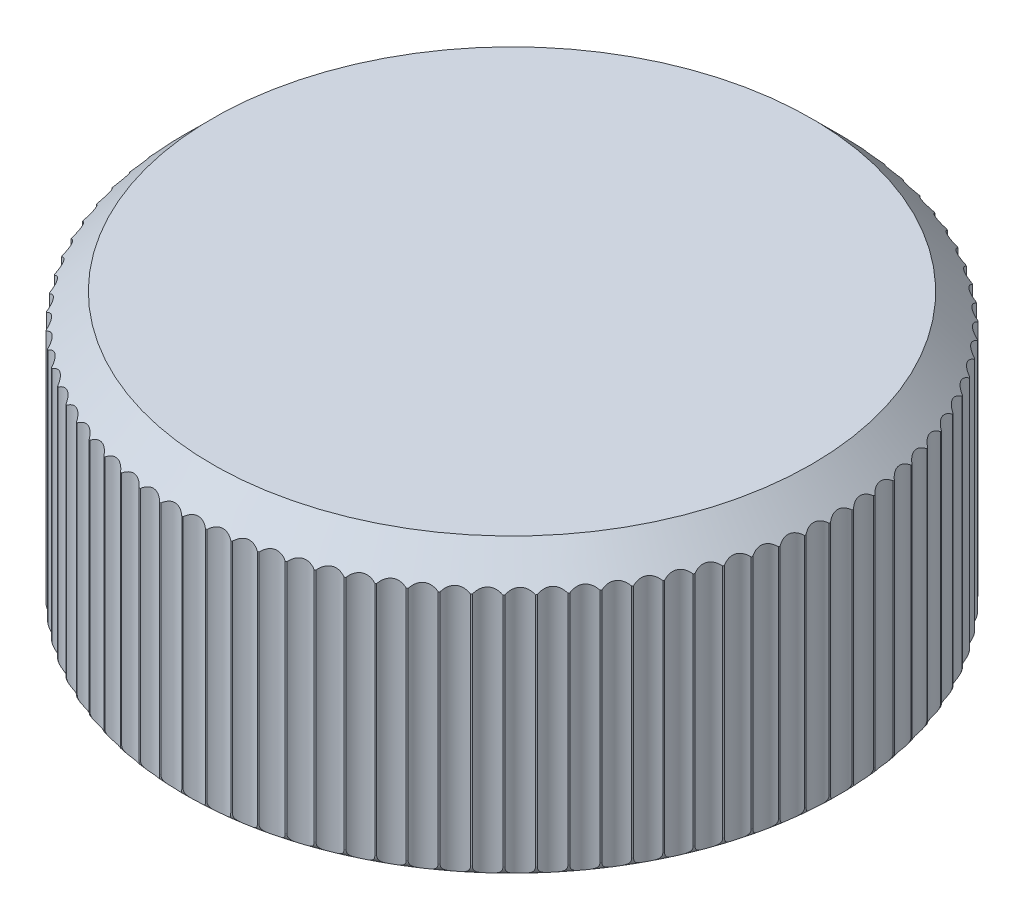
SolidWorks part; units mm, degrees
ref_plane "Ebene vorne" through (0, 0, 0) normal (0, 0, 1) x (1, 0, 0)
ref_plane "Ebene oben" through (0, 0, 0) normal (0, 1, 0) x (1, 0, 0)
ref_plane "Ebene rechts" through (0, 0, 0) normal (1, 0, 0) x (0, 0, -1)
sketch "Skizze1" plane through (0, 0, 0) normal (0, 0, 1) x (1, 0, 0)
  line L0 (0, 8) -> (0, 13.8)
  line L1 (0, 13.8) -> (-15, 13.8)
  line L2 (-16.5, 12.3) -> (-16.5, 0.5)
  line L3 (-16, 0) -> (-15, 0)
  line L4 (-14.5, 0.5) -> (-14.5, 5.5)
  line L5 (-14, 6) -> (-6, 6)
  line L6 (-5.5, 5.5) -> (-5.5, 0.5)
  line L7 (-5, 0) -> (-3, 0)
  line L8 (-3, 0) -> (-3, 7.5)
  line L9 (-2.5, 8) -> (0, 8)
  line L10 (-15, 13.8) -> (-16.5, 12.3)
  arc A0 (-3, 7.5) -> (-2.5, 8) centre (-2.5, 7.5) cw
  arc A1 (-5.5, 0.5) -> (-5, 0) centre (-5, 0.5) ccw
  arc A2 (-6, 6) -> (-5.5, 5.5) centre (-6, 5.5) cw
  arc A3 (-14.5, 5.5) -> (-14, 6) centre (-14, 5.5) cw
  arc A4 (-15, 0) -> (-14.5, 0.5) centre (-15, 0.5) ccw
  arc A5 (-16.5, 0.5) -> (-16, 0) centre (-16, 0.5) ccw
  point P3 (-16.5, 13.8)
  dimension "D1" = 0.5
revolve "Rotation1" add sketch "Skizze1" angle 360 about L0
sketch "Skizze2" plane through (0, 13.8, 0) normal (0, 1, 0) x (1, 0, 0)
  circle A0 centre (0, 0) radius 18.5117
  arc A1 (16.5206, 0.5769) -> (16.5206, -0.5769) centre (17.1752, 0) ccw
  arc A2 (16.5206, -0.5769) -> (16.4401, -1.7279) centre (17.1334, -1.1981) ccw
  arc A3 (16.4401, -1.7279) -> (16.2795, -2.8705) centre (17.0081, -2.3903) ccw
  arc A4 (16.2795, -2.8705) -> (16.0396, -3.9991) centre (16.7999, -3.5709) ccw
  arc A16 (8.7599, -14.0188) -> (7.7607, -14.5957) centre (8.5876, -14.8742) ccw
  arc A17 (7.7607, -14.5957) -> (6.7236, -15.1015) centre (7.5291, -15.437) ccw
  arc A40 (-14.8576, -7.2466) -> (-15.3269, -6.1925) centre (-15.6903, -6.9858) ccw
  arc A41 (-15.3269, -6.1925) -> (-15.7216, -5.1082) centre (-16.1394, -5.8743) ccw
  arc A76 (7.7607, 14.5957) -> (8.7599, 14.0188) centre (8.5876, 14.8742) ccw
  arc A77 (8.7599, 14.0188) -> (9.7165, 13.3736) centre (9.6042, 14.2389) ccw
  arc A78 (9.7165, 13.3736) -> (10.6257, 12.6632) centre (10.5741, 13.5342) ccw
  arc A83 (13.7045, 9.2438) -> (14.3159, 8.2653) centre (14.5654, 9.1015) ccw
  arc A84 (14.3159, 8.2653) -> (14.8576, 7.2466) centre (15.1648, 8.0633) ccw
  arc A89 (16.2795, 2.8705) -> (16.4401, 1.7279) centre (17.0081, 2.3903) ccw
  arc A90 (16.4401, 1.7279) -> (16.5206, 0.5769) centre (17.1334, 1.1981) ccw
  arc A91 (6.7236, 15.1015) -> (7.7607, 14.5957) centre (7.5291, 15.437) ccw
  arc A92 (5.6538, 15.5337) -> (6.7236, 15.1015) centre (6.4339, 15.9246) ccw
  arc A93 (4.5565, 15.8903) -> (5.6538, 15.5337) centre (5.3074, 16.3346) ccw
  arc A94 (3.4369, 16.1694) -> (4.5565, 15.8903) centre (4.1551, 16.665) ccw
  arc A95 (2.3006, 16.3698) -> (3.4369, 16.1694) centre (2.9824, 16.9143) ccw
  arc A96 (1.1531, 16.4904) -> (2.3006, 16.3698) centre (1.7953, 17.0811) ccw
  arc A97 (0, 16.5306) -> (1.1531, 16.4904) centre (0.5994, 17.1647) ccw
  arc A98 (-1.1531, 16.4904) -> (0, 16.5306) centre (-0.5994, 17.1647) ccw
  arc A99 (-2.3006, 16.3698) -> (-1.1531, 16.4904) centre (-1.7953, 17.0811) ccw
  arc A100 (-3.4369, 16.1694) -> (-2.3006, 16.3698) centre (-2.9824, 16.9143) ccw
  arc A101 (-4.5565, 15.8903) -> (-3.4369, 16.1694) centre (-4.1551, 16.665) ccw
  arc A102 (-5.6538, 15.5337) -> (-4.5565, 15.8903) centre (-5.3074, 16.3346) ccw
  arc A103 (-6.7236, 15.1015) -> (-5.6538, 15.5337) centre (-6.4339, 15.9246) ccw
  arc A104 (-7.7607, 14.5957) -> (-6.7236, 15.1015) centre (-7.5291, 15.437) ccw
  arc A105 (-8.7599, 14.0188) -> (-7.7607, 14.5957) centre (-8.5876, 14.8742) ccw
  arc A106 (-9.7165, 13.3736) -> (-8.7599, 14.0188) centre (-9.6042, 14.2389) ccw
  arc A107 (-10.6257, 12.6632) -> (-9.7165, 13.3736) centre (-10.5741, 13.5342) ccw
  arc A108 (-11.4831, 11.8911) -> (-10.6257, 12.6632) centre (-11.4925, 12.7637) ccw
  arc A109 (-12.2847, 11.0611) -> (-11.4831, 11.8911) centre (-12.3548, 11.9309) ccw
  arc A110 (-13.0263, 10.1773) -> (-12.2847, 11.0611) centre (-13.157, 11.04) ccw
  arc A111 (-13.7045, 9.2438) -> (-13.0263, 10.1773) centre (-13.895, 10.0953) ccw
  arc A112 (-14.3159, 8.2653) -> (-13.7045, 9.2438) centre (-14.5654, 9.1015) ccw
  arc A113 (-14.8576, 7.2466) -> (-14.3159, 8.2653) centre (-15.1648, 8.0633) ccw
  arc A114 (-15.3269, 6.1925) -> (-14.8576, 7.2466) centre (-15.6903, 6.9858) ccw
  arc A115 (-15.7216, 5.1082) -> (-15.3269, 6.1925) centre (-16.1394, 5.8743) ccw
  arc A116 (-16.0396, 3.9991) -> (-15.7216, 5.1082) centre (-16.5099, 4.7341) ccw
  arc A117 (-16.2795, 2.8705) -> (-16.0396, 3.9991) centre (-16.7999, 3.5709) ccw
  arc A118 (-16.4401, 1.7279) -> (-16.2795, 2.8705) centre (-17.0081, 2.3903) ccw
  arc A119 (-16.5206, 0.5769) -> (-16.4401, 1.7279) centre (-17.1334, 1.1981) ccw
  arc A120 (-16.5206, -0.5769) -> (-16.5206, 0.5769) centre (-17.1752, 0) ccw
  arc A121 (-16.4401, -1.7279) -> (-16.5206, -0.5769) centre (-17.1334, -1.1981) ccw
  arc A122 (-16.2795, -2.8705) -> (-16.4401, -1.7279) centre (-17.0081, -2.3903) ccw
  arc A123 (-16.0396, -3.9991) -> (-16.2795, -2.8705) centre (-16.7999, -3.5709) ccw
  arc A124 (-15.7216, -5.1082) -> (-16.0396, -3.9991) centre (-16.5099, -4.7341) ccw
  arc A125 (-14.3159, -8.2653) -> (-14.8576, -7.2466) centre (-15.1648, -8.0633) ccw
  arc A126 (-13.7045, -9.2438) -> (-14.3159, -8.2653) centre (-14.5654, -9.1015) ccw
  arc A127 (-13.0263, -10.1773) -> (-13.7045, -9.2438) centre (-13.895, -10.0953) ccw
  arc A128 (-12.2847, -11.0611) -> (-13.0263, -10.1773) centre (-13.157, -11.04) ccw
  arc A129 (-17.2701, -4.3059) -> (-16.2603, -5.5703) centre (-16.5099, -4.7341) ccw [skipped]
  arc A130 (-11.4831, -11.8911) -> (-12.2847, -11.0611) centre (-12.3548, -11.9309) ccw
  arc A131 (-10.6257, -12.6632) -> (-11.4831, -11.8911) centre (-11.4925, -12.7637) ccw
  arc A132 (-9.7165, -13.3736) -> (-10.6257, -12.6632) centre (-10.5741, -13.5342) ccw
  arc A133 (-8.7599, -14.0188) -> (-9.7165, -13.3736) centre (-9.6042, -14.2389) ccw
  arc A134 (-7.7607, -14.5957) -> (-8.7599, -14.0188) centre (-8.5876, -14.8742) ccw
  arc A135 (-6.7236, -15.1015) -> (-7.7607, -14.5957) centre (-7.5291, -15.437) ccw
  arc A136 (-5.6538, -15.5337) -> (-6.7236, -15.1015) centre (-6.4339, -15.9246) ccw
  arc A137 (-4.5565, -15.8903) -> (-5.6538, -15.5337) centre (-5.3074, -16.3346) ccw
  arc A138 (-3.4369, -16.1694) -> (-4.5565, -15.8903) centre (-4.1551, -16.665) ccw
  arc A139 (-2.3006, -16.3698) -> (-3.4369, -16.1694) centre (-2.9824, -16.9143) ccw
  arc A140 (-1.1531, -16.4904) -> (-2.3006, -16.3698) centre (-1.7953, -17.0811) ccw
  arc A141 (0, -16.5306) -> (-1.1531, -16.4904) centre (-0.5994, -17.1647) ccw
  arc A142 (1.1531, -16.4904) -> (0, -16.5306) centre (0.5994, -17.1647) ccw
  arc A143 (2.3006, -16.3698) -> (1.1531, -16.4904) centre (1.7953, -17.0811) ccw
  arc A144 (3.4369, -16.1694) -> (2.3006, -16.3698) centre (2.9824, -16.9143) ccw
  arc A145 (4.5565, -15.8903) -> (3.4369, -16.1694) centre (4.1551, -16.665) ccw
  arc A146 (5.6538, -15.5337) -> (4.5565, -15.8903) centre (5.3074, -16.3346) ccw
  arc A147 (6.7236, -15.1015) -> (5.6538, -15.5337) centre (6.4339, -15.9246) ccw
  arc A148 (9.7165, -13.3736) -> (8.7599, -14.0188) centre (9.6042, -14.2389) ccw
  arc A149 (10.6257, -12.6632) -> (9.7165, -13.3736) centre (10.5741, -13.5342) ccw
  arc A150 (11.4831, -11.8911) -> (10.6257, -12.6632) centre (11.4925, -12.7637) ccw
  arc A151 (12.2847, -11.0611) -> (11.4831, -11.8911) centre (12.3548, -11.9309) ccw
  arc A152 (13.0263, -10.1773) -> (12.2847, -11.0611) centre (13.157, -11.04) ccw
  arc A153 (13.7045, -9.2438) -> (13.0263, -10.1773) centre (13.895, -10.0953) ccw
  arc A154 (14.3159, -8.2653) -> (13.7045, -9.2438) centre (14.5654, -9.1015) ccw
  arc A155 (14.8576, -7.2466) -> (14.3159, -8.2653) centre (15.1648, -8.0633) ccw
  arc A156 (15.3269, -6.1925) -> (14.8576, -7.2466) centre (15.6903, -6.9858) ccw
  arc A157 (15.7216, -5.1082) -> (15.3269, -6.1925) centre (16.1394, -5.8743) ccw
  arc A158 (16.0396, -3.9991) -> (15.7216, -5.1082) centre (16.5099, -4.7341) ccw
  arc A159 (16.0396, 3.9991) -> (16.2795, 2.8705) centre (16.7999, 3.5709) ccw
  arc A160 (15.7216, 5.1082) -> (16.0396, 3.9991) centre (16.5099, 4.7341) ccw
  arc A161 (15.3269, 6.1925) -> (15.7216, 5.1082) centre (16.1394, 5.8743) ccw
  arc A162 (14.8576, 7.2466) -> (15.3269, 6.1925) centre (15.6903, 6.9858) ccw
  arc A163 (13.0263, 10.1773) -> (13.7045, 9.2438) centre (13.895, 10.0953) ccw
  arc A164 (12.2847, 11.0611) -> (13.0263, 10.1773) centre (13.157, 11.04) ccw
  arc A165 (11.4831, 11.8911) -> (12.2847, 11.0611) centre (12.3548, 11.9309) ccw
  arc A166 (10.6257, 12.6632) -> (11.4831, 11.8911) centre (11.4925, 12.7637) ccw
  arc A167 (13.2271, 11.9098) -> (12.3641, 12.8034) centre (12.3548, 11.9309) ccw [skipped]
  arc A168 (12.3641, 12.8034) -> (11.4409, 13.6347) centre (11.4925, 12.7637) ccw [skipped]
  arc A169 (14.0257, 10.9581) -> (13.2271, 11.9098) centre (13.157, 11.04) ccw [skipped]
  arc A170 (14.7559, 9.953) -> (14.0257, 10.9581) centre (13.895, 10.0953) ccw [skipped]
  arc A171 (16.5028, 6.6676) -> (15.9975, 7.8025) centre (15.6903, 6.9858) ccw [skipped]
  arc A172 (16.9277, 5.5001) -> (16.5028, 6.6676) centre (16.1394, 5.8743) ccw [skipped]
  arc A173 (17.2701, 4.3059) -> (16.9277, 5.5001) centre (16.5099, 4.7341) ccw [skipped]
  arc A174 (17.5284, 3.0907) -> (17.2701, 4.3059) centre (16.7999, 3.5709) ccw [skipped]
  arc A175 (16.9277, -5.5001) -> (17.2701, -4.3059) centre (16.5099, -4.7341) ccw [skipped]
  arc A176 (16.5028, -6.6676) -> (16.9277, -5.5001) centre (16.1394, -5.8743) ccw [skipped]
  arc A177 (15.9975, -7.8025) -> (16.5028, -6.6676) centre (15.6903, -6.9858) ccw [skipped]
  arc A178 (15.4143, -8.8994) -> (15.9975, -7.8025) centre (15.1648, -8.0633) ccw [skipped]
  arc A179 (14.7559, -9.953) -> (15.4143, -8.8994) centre (14.5654, -9.1015) ccw [skipped]
  arc A180 (14.0257, -10.9581) -> (14.7559, -9.953) centre (13.895, -10.0953) ccw [skipped]
  arc A181 (13.2271, -11.9098) -> (14.0257, -10.9581) centre (13.157, -11.04) ccw [skipped]
  arc A182 (12.3641, -12.8034) -> (13.2271, -11.9098) centre (12.3548, -11.9309) ccw [skipped]
  arc A183 (11.4409, -13.6347) -> (12.3641, -12.8034) centre (11.4925, -12.7637) ccw [skipped]
  arc A184 (10.4619, -14.3996) -> (11.4409, -13.6347) centre (10.5741, -13.5342) ccw [skipped]
  arc A185 (9.4319, -15.0943) -> (10.4619, -14.3996) centre (9.6042, -14.2389) ccw [skipped]
  arc A186 (4.906, -17.1093) -> (6.0876, -16.7254) centre (5.3074, -16.3346) ccw [skipped]
  arc A187 (3.7006, -17.4099) -> (4.906, -17.1093) centre (4.1551, -16.665) ccw [skipped]
  arc A188 (2.4771, -17.6256) -> (3.7006, -17.4099) centre (2.9824, -16.9143) ccw [skipped]
  arc A189 (1.2416, -17.7555) -> (2.4771, -17.6256) centre (1.7953, -17.0811) ccw [skipped]
  arc A190 (0, -17.7988) -> (1.2416, -17.7555) centre (0.5994, -17.1647) ccw [skipped]
  arc A191 (-1.2416, -17.7555) -> (0, -17.7988) centre (-0.5994, -17.1647) ccw [skipped]
  arc A192 (6.0876, -16.7254) -> (7.2394, -16.2601) centre (6.4339, -15.9246) ccw [skipped]
  arc A193 (-2.4771, -17.6256) -> (-1.2416, -17.7555) centre (-1.7953, -17.0811) ccw [skipped]
  arc A194 (-3.7006, -17.4099) -> (-2.4771, -17.6256) centre (-2.9824, -16.9143) ccw [skipped]
  arc A195 (-4.906, -17.1093) -> (-3.7006, -17.4099) centre (-4.1551, -16.665) ccw [skipped]
  arc A196 (-15.9975, -7.8025) -> (-15.4143, -8.8994) centre (-15.1648, -8.0633) ccw [skipped]
  arc A197 (-6.0876, -16.7254) -> (-4.906, -17.1093) centre (-5.3074, -16.3346) ccw [skipped]
  arc A198 (-7.2394, -16.2601) -> (-6.0876, -16.7254) centre (-6.4339, -15.9246) ccw [skipped]
  arc A199 (-8.3561, -15.7154) -> (-7.2394, -16.2601) centre (-7.5291, -15.437) ccw [skipped]
  arc A200 (-9.4319, -15.0943) -> (-8.3561, -15.7154) centre (-8.5876, -14.8742) ccw [skipped]
  arc A201 (-10.4619, -14.3996) -> (-9.4319, -15.0943) centre (-9.6042, -14.2389) ccw [skipped]
  arc A202 (-11.4409, -13.6347) -> (-10.4619, -14.3996) centre (-10.5741, -13.5342) ccw [skipped]
  arc A203 (-12.3641, -12.8034) -> (-11.4409, -13.6347) centre (-11.4925, -12.7637) ccw [skipped]
  arc A204 (-13.2271, -11.9098) -> (-12.3641, -12.8034) centre (-12.3548, -11.9309) ccw [skipped]
  arc A205 (-14.0257, -10.9581) -> (-13.2271, -11.9098) centre (-13.157, -11.04) ccw [skipped]
  arc A206 (-14.7559, -9.953) -> (-14.0257, -10.9581) centre (-13.895, -10.0953) ccw [skipped]
  arc A207 (-15.4143, -8.8994) -> (-14.7559, -9.953) centre (-14.5654, -9.1015) ccw [skipped]
  arc A208 (-17.5284, -3.0907) -> (-17.2701, -4.3059) centre (-16.7999, -3.5709) ccw [skipped]
  arc A209 (-17.7013, -1.8605) -> (-17.5284, -3.0907) centre (-17.0081, -2.3903) ccw [skipped]
  arc A210 (-17.788, -0.6212) -> (-17.7013, -1.8605) centre (-17.1334, -1.1981) ccw [skipped]
  arc A211 (-17.788, 0.6212) -> (-17.788, -0.6212) centre (-17.1752, 0) ccw [skipped]
  arc A212 (-17.7013, 1.8605) -> (-17.788, 0.6212) centre (-17.1334, 1.1981) ccw [skipped]
  arc A213 (-17.5284, 3.0907) -> (-17.7013, 1.8605) centre (-17.0081, 2.3903) ccw [skipped]
  arc A214 (-17.2701, 4.3059) -> (-17.5284, 3.0907) centre (-16.7999, 3.5709) ccw [skipped]
  arc A215 (-16.9277, 5.5001) -> (-17.2701, 4.3059) centre (-16.5099, 4.7341) ccw [skipped]
  arc A216 (-16.5028, 6.6676) -> (-16.9277, 5.5001) centre (-16.1394, 5.8743) ccw [skipped]
  arc A217 (-15.9975, 7.8025) -> (-16.5028, 6.6676) centre (-15.6903, 6.9858) ccw [skipped]
  arc A218 (-15.4143, 8.8994) -> (-15.9975, 7.8025) centre (-15.1648, 8.0633) ccw [skipped]
  arc A219 (-14.7559, 9.953) -> (-15.4143, 8.8994) centre (-14.5654, 9.1015) ccw [skipped]
  arc A220 (-14.0257, 10.9581) -> (-14.7559, 9.953) centre (-13.895, 10.0953) ccw [skipped]
  arc A221 (-13.2271, 11.9098) -> (-14.0257, 10.9581) centre (-13.157, 11.04) ccw [skipped]
  arc A222 (-12.3641, 12.8034) -> (-13.2271, 11.9098) centre (-12.3548, 11.9309) ccw [skipped]
  arc A223 (-11.4409, 13.6347) -> (-12.3641, 12.8034) centre (-11.4925, 12.7637) ccw [skipped]
  arc A224 (-10.4619, 14.3996) -> (-11.4409, 13.6347) centre (-10.5741, 13.5342) ccw [skipped]
  arc A225 (-9.4319, 15.0943) -> (-10.4619, 14.3996) centre (-9.6042, 14.2389) ccw [skipped]
  arc A226 (-8.3561, 15.7154) -> (-9.4319, 15.0943) centre (-8.5876, 14.8742) ccw [skipped]
  arc A227 (-7.2394, 16.2601) -> (-8.3561, 15.7154) centre (-7.5291, 15.437) ccw [skipped]
  arc A228 (-6.0876, 16.7254) -> (-7.2394, 16.2601) centre (-6.4339, 15.9246) ccw [skipped]
  arc A229 (-3.7006, 17.4099) -> (-4.906, 17.1093) centre (-4.1551, 16.665) ccw [skipped]
  arc A230 (-4.906, 17.1093) -> (-6.0876, 16.7254) centre (-5.3074, 16.3346) ccw [skipped]
  arc A231 (-2.4771, 17.6256) -> (-3.7006, 17.4099) centre (-2.9824, 16.9143) ccw [skipped]
  arc A232 (0, 17.7988) -> (-1.2416, 17.7555) centre (-0.5994, 17.1647) ccw [skipped]
  arc A233 (-1.2416, 17.7555) -> (-2.4771, 17.6256) centre (-1.7953, 17.0811) ccw [skipped]
  arc A234 (1.2416, 17.7555) -> (0, 17.7988) centre (0.5994, 17.1647) ccw [skipped]
  arc A235 (2.4771, 17.6256) -> (1.2416, 17.7555) centre (1.7953, 17.0811) ccw [skipped]
  arc A236 (3.7006, 17.4099) -> (2.4771, 17.6256) centre (2.9824, 16.9143) ccw [skipped]
  arc A237 (4.906, 17.1093) -> (3.7006, 17.4099) centre (4.1551, 16.665) ccw [skipped]
  arc A238 (6.0876, 16.7254) -> (4.906, 17.1093) centre (5.3074, 16.3346) ccw [skipped]
  arc A239 (7.2394, 16.2601) -> (6.0876, 16.7254) centre (6.4339, 15.9246) ccw [skipped]
  arc A240 (8.3561, 15.7154) -> (7.2394, 16.2601) centre (7.5291, 15.437) ccw [skipped]
  point P3 (0, 0)
  point P185 (0, 0)
  dimension "D1" = 90
extrude "Schnitt-Linear austragen1" cut sketch "Skizze2" against normal through all
